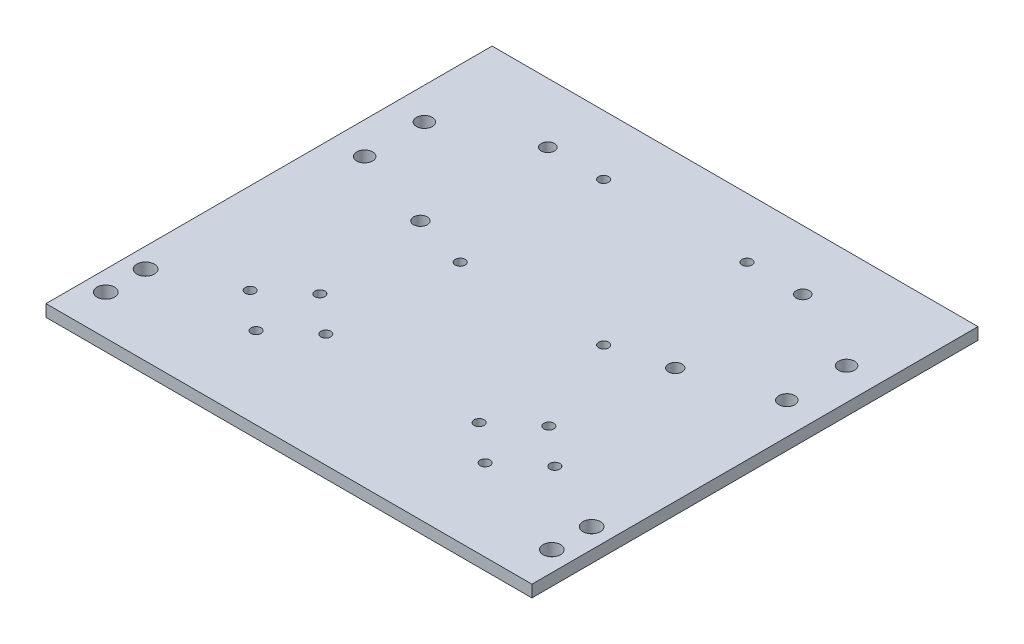
SolidWorks part; units mm, degrees
ref_plane "Front Plane" through (0, 0, 0) normal (0, 0, 1) x (1, 0, 0)
ref_plane "Top Plane" through (0, 0, 0) normal (0, 1, 0) x (1, 0, 0)
ref_plane "Right Plane" through (0, 0, 0) normal (1, 0, 0) x (0, 0, -1)
sketch "Sketch1" plane through (0, 0, 0) normal (0, 1, 0) x (1, 0, 0)
  line L1 (-61, 56) -> (61, 56)
  line L2 (-61, 56) -> (-61, -56)
  line L3 (-61, -56) -> (61, -56)
  line L4 (61, 56) -> (61, -56)
  line L5 (-61, 56) -> (61, -56) construction
  line L6 (-61, -56) -> (61, 56) construction
  point P0 (0, 0)
  dimension "D1" = 122
  dimension "D2" = 112
extrude "Boss-Extrude1" add sketch "Sketch1" along normal blind 3
sketch "Sketch3" plane through (0, 3, 0) normal (0, 1, 0) x (1, 0, 0)
  line L0 (61, 56) -> (-61, 56) construction
  line L1 (-61, 56) -> (-61, -56) construction
  line L2 (0, -1.65) -> (0, 1.65) construction
  circle A0 centre (-53, 31) radius 2
  circle A1 centre (-53, 16) radius 2
  circle A2 centre (53, 16) radius 2
  circle A3 centre (53, 31) radius 2
  dimension "D5" = 4
  dimension "D6" = 4
  dimension "D1" = 25
  dimension "D2" = 15
  dimension "D3" = 8
  dimension "D4" = 8
extrude "Cut-Extrude2" cut sketch "Sketch3" against normal blind 10
sketch "Sketch4" plane through (0, 3, 0) normal (0, 1, 0) x (1, 0, 0)
  line L0 (61, 56) -> (-61, 56) construction
  line L1 (0, -1.65) -> (0, 1.65) construction
  circle A0 centre (-18, 41) radius 1.25
  circle A1 centre (-18, 5) radius 1.25
  circle A2 centre (18, 5) radius 1.25
  circle A3 centre (18, 41) radius 1.25
  dimension "D3" = 2.5
  dimension "D4" = 2.5
  dimension "D1" = 15
  dimension "D2" = 36
  dimension "D5" = 18
extrude "Cut-Extrude3" cut sketch "Sketch4" against normal blind 23
sketch "Sketch5" plane through (0, 3, 0) normal (0, 1, 0) x (1, 0, 0)
  line L0 (61, 56) -> (-61, 56) construction
  line L1 (0, -1.65) -> (0, 1.65) construction
  line L2 (-38.25, -27.5) -> (-19.25, -27.5) construction
  line L3 (-28.75, -19.5) -> (-28.75, -35.5) construction
  circle A0 centre (-38.25, -27.5) radius 1.25
  circle A1 centre (-28.75, -19.5) radius 1.25
  circle A2 centre (-28.75, -35.5) radius 1.25
  circle A3 centre (-19.25, -27.5) radius 1.25
  circle A4 centre (38.25, -27.5) radius 1.25
  circle A5 centre (19.25, -27.5) radius 1.25
  circle A6 centre (28.75, -35.5) radius 1.25
  circle A7 centre (28.75, -19.5) radius 1.25
  point P0 (-28.75, -27.5)
  point P1 (28.75, -27.5)
  dimension "D9" = 2.5
  dimension "D10" = 2.5
  dimension "D1" = 83.5
  dimension "D2" = 83.5
  dimension "D3" = 28.75
  dimension "D4" = 28.75
  dimension "D5" = 16
  dimension "D6" = 8
  dimension "D7" = 19
  dimension "D8" = 9.5
extrude "Cut-Extrude4" cut sketch "Sketch5" against normal blind 23
sketch "Sketch6" plane through (0, 3, 0) normal (0, 1, 0) x (1, 0, 0)
  line L0 (0, -1.65) -> (0, 1.65) construction
  circle A0 centre (-32, 41) radius 1.65
  circle A1 centre (-18, 41) radius 1.25 construction
  circle A2 centre (-32, 9) radius 1.7227
  circle A3 centre (32, 9) radius 1.7227
  circle A4 centre (32, 41) radius 1.65
  dimension "D2" = 3.3
  dimension "D1" = 32
  dimension "D3" = 0
  dimension "D4" = 32
extrude "Cut-Extrude5" cut sketch "Sketch6" against normal blind 10
sketch "Sketch7" plane through (0, 3, 0) normal (0, 1, 0) x (1, 0, 0)
  line L0 (-61, 56) -> (-61, -56) construction
  line L1 (-61, -56) -> (61, -56) construction
  circle A0 centre (-56, -46) radius 2.2
  circle A1 centre (-56, -36) radius 2.2
  dimension "D4" = 4.4
  dimension "D5" = 4.4
  dimension "D1" = 5
  dimension "D2" = 5
  dimension "D3" = 10
  dimension "D6" = 10
extrude "Cut-Extrude6" cut sketch "Sketch7" against normal blind 10
mirror "Mirror1" about plane through (0, 0, 0) normal (1, 0, 0) of "Cut-Extrude6"
equation "\"D6@Sketch3\"=\"D5@Sketch3\""
equation "\"D4@Sketch4\"=\"D3@Sketch4\""
equation "\"D2@Sketch5\"=\"D1@Sketch5\""
equation "\"D4@Sketch5\"=\"D3@Sketch5\""
equation "\"D6@Sketch5\"=\"D5@Sketch5\"/2"
equation "\"D8@Sketch5\"=\"D7@Sketch5\"/2"
